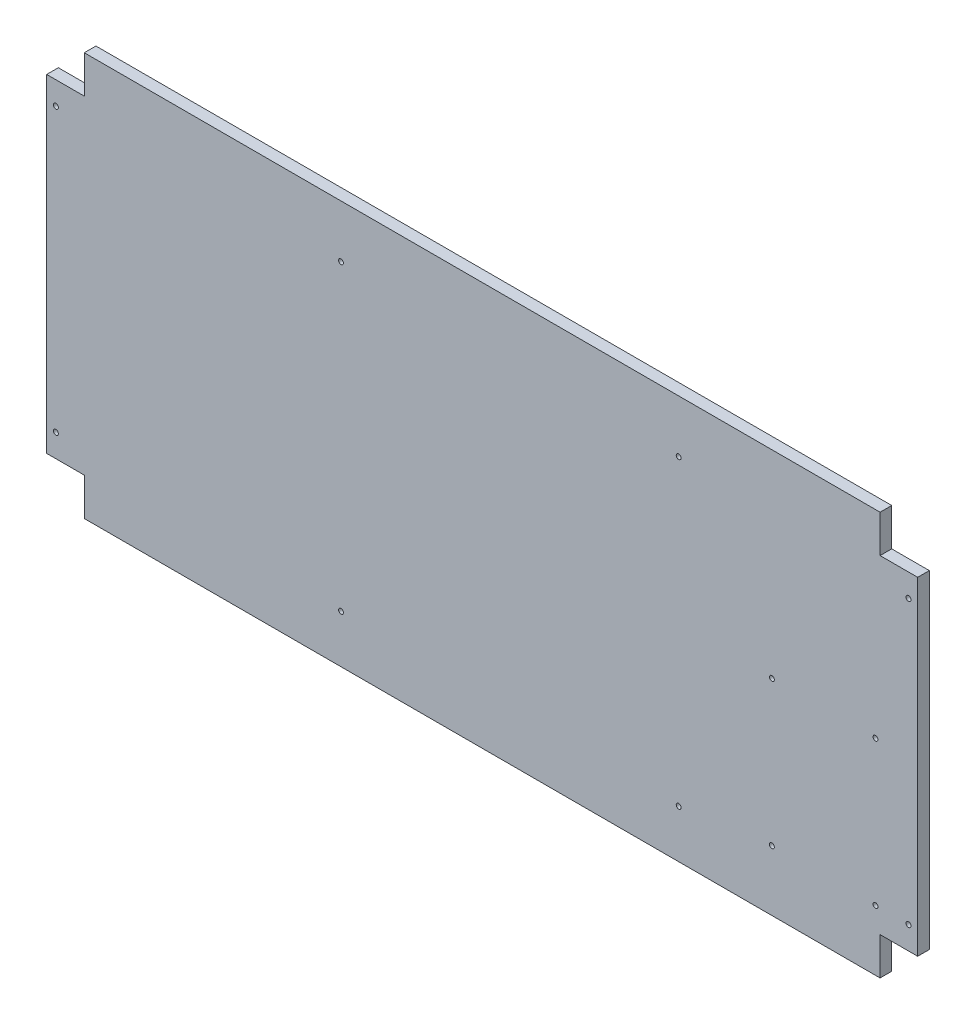
SolidWorks part; units mm, degrees
ref_plane "Front Plane" through (0, 0, 0) normal (0, 0, 1) x (1, 0, 0)
ref_plane "Top Plane" through (0, 0, 0) normal (0, 1, 0) x (1, 0, 0)
ref_plane "Right Plane" through (0, 0, 0) normal (1, 0, 0) x (0, 0, -1)
sketch "Sketch2" plane through (0, 0, 0) normal (0, 0, 1) x (1, 0, 0)
  line L1 (-475, -220) -> (475, -220)
  line L2 (-475, -220) -> (-475, 220)
  line L3 (-475, 220) -> (475, 220)
  line L4 (475, -220) -> (475, 220)
  line L5 (-475, -220) -> (475, 220) construction
  line L6 (-475, 220) -> (475, -220) construction
  point P0 (0, 0)
  dimension "D1" = 950
  dimension "D2" = 440
extrude "Boss-Extrude1" add sketch "Sketch2" along normal blind 12.7
sketch "Sketch3" plane through (0, 0, 12.7) normal (0, 0, 1) x (1, 0, 0)
  line L0 (0, 220) -> (0, -220) construction
  line L1 (-475, 220) -> (-434, 220)
  line L2 (-475, 220) -> (-475, 179)
  line L3 (-475, 179) -> (-434, 179)
  line L4 (-434, 220) -> (-434, 179)
  line L5 (-475, 220) -> (-434, 179) construction
  line L6 (-475, 179) -> (-434, 220) construction
  line L7 (475, 220) -> (-475, 220) construction
  line L8 (-475, -220) -> (475, -220) construction
  line L9 (-475, 0) -> (475, 0) construction
  line L10 (-475, 220) -> (-475, -220) construction
  line L11 (475, -220) -> (475, 220) construction
  line L12 (475, 179) -> (434, 220) construction
  line L13 (475, 220) -> (434, 179) construction
  line L14 (434, 220) -> (434, 179)
  line L15 (475, 179) -> (434, 179)
  line L16 (475, 220) -> (475, 179)
  line L17 (475, 220) -> (434, 220)
  line L18 (475, -220) -> (434, -179) construction
  line L19 (475, -179) -> (434, -220) construction
  line L20 (475, -220) -> (434, -220)
  line L21 (475, -220) -> (475, -179)
  line L22 (434, -220) -> (434, -179)
  line L23 (475, -179) -> (434, -179)
  line L24 (-475, -179) -> (-434, -220) construction
  line L25 (-475, -220) -> (-434, -179) construction
  line L26 (-434, -220) -> (-434, -179)
  line L27 (-475, -179) -> (-434, -179)
  line L28 (-475, -220) -> (-475, -179)
  line L29 (-475, -220) -> (-434, -220)
  point P4 (-454.5, 199.5)
  point P22 (454.5, 199.5)
  point P27 (454.5, -199.5)
  point P32 (-454.5, -199.5)
  dimension "D1" = 41
  dimension "D2" = 41
extrude "Cut-Extrude1" cut sketch "Sketch3" against normal up to next
sketch "Sketch4" plane through (0, 0, 12.7) normal (0, 0, 1) x (1, 0, 0)
  line L0 (-465, 179) -> (-465, -179) construction
  line L1 (-475, 179) -> (-434, 179) construction
  line L2 (-434, -179) -> (-475, -179) construction
  line L3 (0, 220) -> (0, -220) construction
  line L4 (434, 220) -> (-434, 220) construction
  line L5 (-434, -220) -> (434, -220) construction
  line L6 (0, 0) -> (-475, 0) construction
  line L7 (-475, 179) -> (-475, -179) construction
  circle A0 centre (-465, -154) radius 2.75
  circle A1 centre (-465, 154) radius 2.75
  circle A2 centre (465, -154) radius 2.75
  circle A3 centre (465, 154) radius 2.75
  dimension "D1" = 5.5
  dimension "D2" = 25
  dimension "D3" = 10
extrude "Cut-Extrude2" cut sketch "Sketch4" against normal up to next
sketch "Sketch6" plane through (0, 0, 12.7) normal (0, 0, 1) x (1, 0, 0)
  circle A0 centre (-153.9852, -167.6051) radius 2.665
  circle A1 centre (214.3148, -167.6051) radius 2.665
  circle A2 centre (214.3148, 162.5949) radius 2.665
  circle A3 centre (-153.9852, 162.5949) radius 2.665
  dimension "D1" = 5.33
extrude "Cut-Extrude3" cut sketch "Sketch6" against normal up to next
sketch "Sketch7" plane through (0, 0, 12.7) normal (0, 0, 1) x (1, 0, 0)
  circle A0 centre (429, 4) radius 2.665
  circle A1 centre (429, -154) radius 2.665
  circle A2 centre (316, 4) radius 2.665
  circle A3 centre (316, -154) radius 2.665
  dimension "D1" = 5.33
extrude "Cut-Extrude4" cut sketch "Sketch7" against normal up to next
